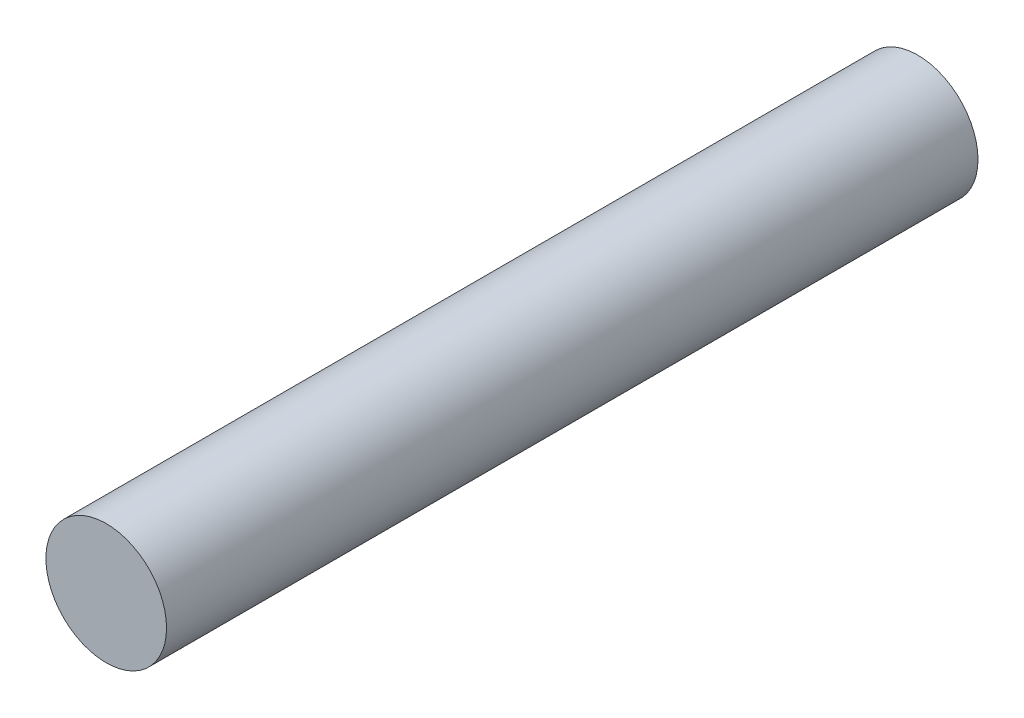
SolidWorks part; units mm, degrees
ref_plane "Front Plane" through (0, 0, 0) normal (0, 0, 1) x (1, 0, 0)
ref_plane "Top Plane" through (0, 0, 0) normal (0, 1, 0) x (1, 0, 0)
ref_plane "Right Plane" through (0, 0, 0) normal (1, 0, 0) x (0, 0, -1)
sketch "Sketch1" plane through (0, 0, 0) normal (0, 0, 1) x (1, 0, 0)
  circle A0 centre (0, 0) radius 6.25
  dimension "D1" = 12.5
extrude "Boss-Extrude1" add sketch "Sketch1" along normal blind 84.07
